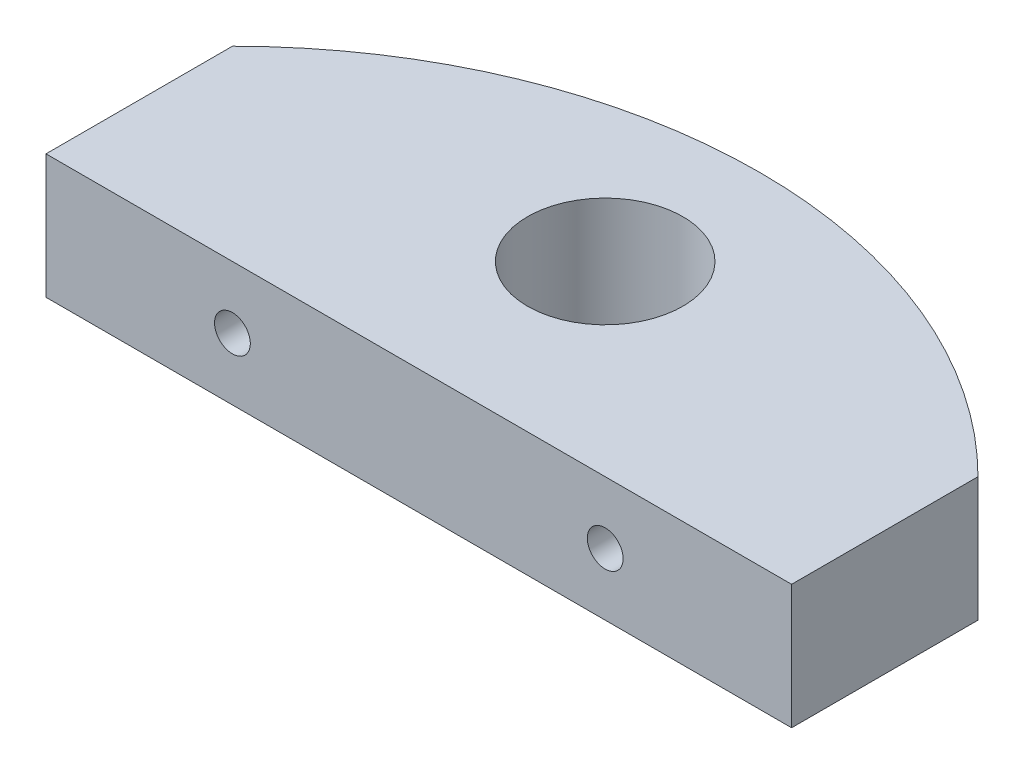
SolidWorks part; units mm, degrees
ref_plane "Front Plane" through (0, 0, 0) normal (0, 0, 1) x (1, 0, 0)
ref_plane "Top Plane" through (0, 0, 0) normal (0, 1, 0) x (1, 0, 0)
ref_plane "Right Plane" through (0, 0, 0) normal (1, 0, 0) x (0, 0, -1)
sketch "Sketch2" plane through (0, 0, 0) normal (0, 1, 0) x (1, 0, 0)
  line L0 (0, 0) -> (-76.2, 0)
  line L1 (-76.2, 0) -> (-76.2, 19.05)
  line L3 (0, 19.05) -> (0, 0)
  line L4 (-76.2, 19.05) -> (0, 19.05) construction
  arc A2 (-76.2, 19.05) -> (0, 19.05) centre (-38.1, -19.05) cw
  dimension "D2" = 76.2
  dimension "D3" = 19.05
extrude "Boss-Extrude1" add sketch "Sketch2" along normal blind 12.7
sketch "Sketch3" plane through (0, 12.7, 0) normal (0, 1, 0) x (1, 0, 0)
  line L0 (-38.1, 0) -> (-38.1, 34.8315) construction
  line L1 (0, 19.05) -> (-76.2, 19.05) construction
  line L2 (-76.2, 0) -> (0, 0) construction
  arc A0 (0, 19.05) -> (-76.2, 19.05) centre (-38.1, -19.05) ccw construction
hole_wizard "5/8 (0.6250) Dowel Hole2" positions "Sketch9" profile "Sketch8" hole size "5/8" standard "ANSI Inch" end condition through all
sketch "Sketch9" plane through (0, 12.7, 0) normal (0, 1, 0) x (1, 0, 0)
  line L0 (0, 19.05) -> (-76.2, 19.05) construction
  point P0 (-38.1, 19.05)
sketch "Sketch8" plane through (-38.1, 12.7, -19.05) normal (1, 0, 0) x (0, 0, 1)
  line L0 (0, 0) -> (0, 12.7)
  line L1 (0, 12.7) -> (7.9375, 12.7)
  line L2 (7.9375, 12.7) -> (7.9375, 0)
  line L5 (7.9375, 0) -> (0, 0)
  line L11 (0, -6.35) -> (0, 107.95) construction
  dimension "Thru Hole Dia." = 15.875
  dimension "Thru Hole Depth" = 12.7
sketch "Sketch10" plane through (0, 0, 0) normal (0, 0, 1) x (1, 0, 0)
  line L0 (-76.2, 0) -> (0, 12.7) construction
  line L1 (-76.2, 12.7) -> (0, 0) construction
  line L2 (-38.1, 6.35) -> (-76.2, 6.35) construction
  line L3 (-76.2, 12.7) -> (-76.2, 0) construction
  line L4 (-57.15, 6.35) -> (-57.15, 12.7) construction
  line L7 (-38.1, 6.35) -> (0, 6.35) construction
  line L8 (0, 12.7) -> (0, 0) construction
  line L9 (0, 12.7) -> (-76.2, 12.7) construction
  line L10 (-19.05, 6.35) -> (-19.05, 12.7) construction
  line L11 (-57.15, 6.35) -> (-57.15, 0) construction
  line L12 (-76.2, 0) -> (0, 0) construction
  line L15 (-19.05, 6.35) -> (-19.05, 0) construction
ref_plane "Plane1" through (0, 0, -32.5882) normal (0, 0, 1) x (1, 0, 0)
hole_wizard "CSK for #6 Flat Head Machine Screw (100)3" positions "Sketch22" profile "Sketch20" countersink size "#6" standard "ANSI Inch" end condition through all
sketch "Sketch22" plane through (0, 0, -32.5882) normal (0, 0, 1) x (1, 0, 0)
  point P0 (-19.05, 6.35)
  point P3 (-57.15, 6.35)
sketch "Sketch20" plane through (-19.05, 6.35, -32.5882) normal (1, 0, 0) x (0, 1, 0)
  line L0 (0, 0) -> (0, 32.5882)
  line L1 (0, 32.5882) -> (1.8288, 32.5882)
  line L2 (1.8288, 32.5882) -> (1.8288, 1.4386)
  line L3 (1.8288, 1.4386) -> (3.5433, 0)
  line L5 (3.5433, 0) -> (0, 0)
  line L6 (-1.8288, 1.4386) -> (-3.5433, 0) construction
  line L11 (0, -6.35) -> (0, 107.95) construction
  dimension "Thru Hole Dia." = 3.6576
  dimension "Thru Hole Depth" = 32.5882
  dimension "Near C'Sink Dia." = 7.0866
  dimension "Near C'Sink Angle" = 100
